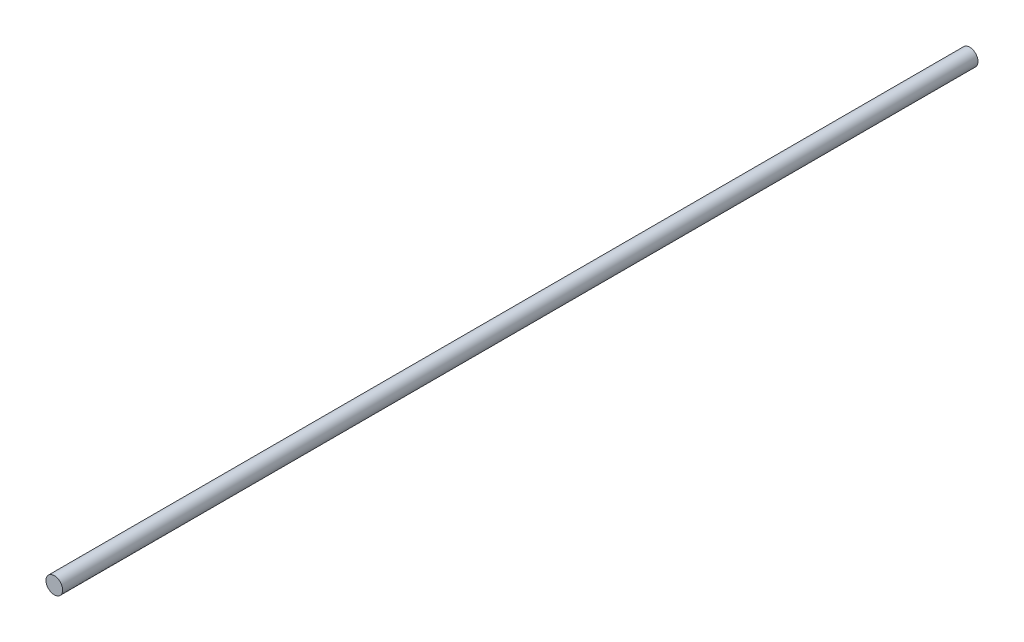
SolidWorks part; units mm, degrees
material "Galvanized Steel"
ref_plane "Front Plane" through (0, 0, 0) normal (0, 0, 1) x (1, 0, 0)
ref_plane "Top Plane" through (0, 0, 0) normal (0, 1, 0) x (1, 0, 0)
ref_plane "Right Plane" through (0, 0, 0) normal (1, 0, 0) x (0, 0, -1)
sketch "Sketch1" plane through (0, 0, 0) normal (0, 0, 1) x (1, 0, 0)
  circle A0 centre (0, 0) radius 5
extrude "Boss-Extrude1" add sketch "Sketch1" along normal blind 550
ref_plane "Plane1" through (0, 5, 0) normal (0, 1, 0) x (1, 0, 0)
sketch "Sketch2" plane through (0, 5, 0) normal (0, 1, 0) x (1, 0, 0)
  line L0 (5, -550) -> (5, 0) construction
  line L1 (-5, -550) -> (5, -550)
  line L2 (-5, -550) -> (-5, -530)
  line L3 (-5, -530) -> (5, -530)
  line L4 (5, -550) -> (5, -530)
  line L5 (-5, 0) -> (-5, -550) construction
  line L6 (-5, -450) -> (5, -450)
  line L7 (-5, -450) -> (-5, -412.6915)
  line L8 (-5, -412.6915) -> (5, -412.6915)
  line L9 (5, -450) -> (5, -412.6915)
  dimension "D1" = 20
  dimension "D2" = 100
extrude "Cut-Extrude1" [suppressed] cut sketch "Sketch2" against normal blind 2.5
ref_plane "Plane2" through (0, 0, 250) normal (0, 0, 1) x (1, 0, 0)
mirror "Mirror1" [suppressed] about plane through (0, 0, 250) normal (0, 0, 1)
